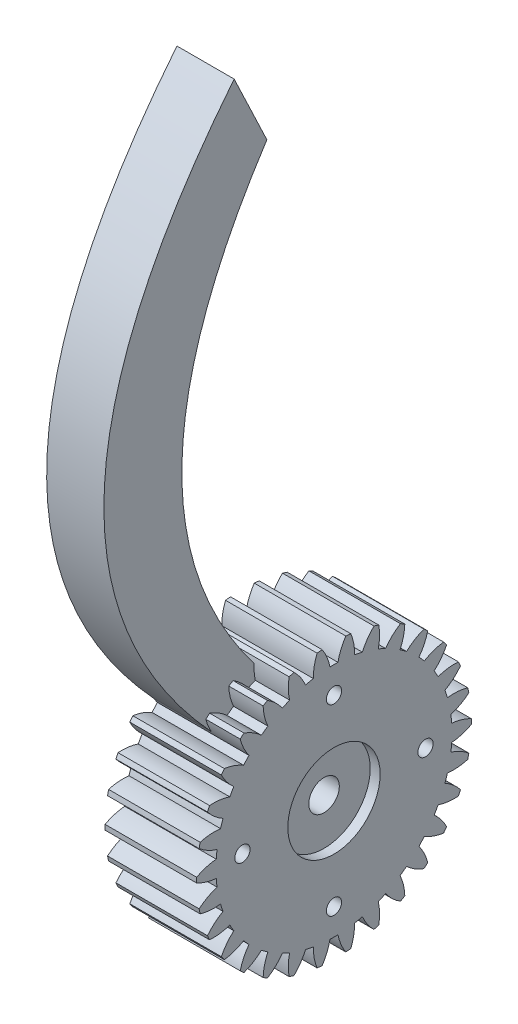
SolidWorks part; units mm, degrees
material "Nylon 101"
ref_plane "Plane1" through (0, 0, 0) normal (0, 0, 1) x (1, 0, 0)
ref_plane "Plane2" through (0, 0, 0) normal (0, 1, 0) x (1, 0, 0)
ref_plane "Plane3" through (0, 0, 0) normal (1, 0, 0) x (0, 0, -1)
other "Configuration Table"
sketch "HoldingSke" plane through (0, 0, 0) normal (0, 1, 0) x (1, 0, 0)
  line L0 (0, 0) -> (0.7698, -0.4444)
  line L1 (-15, 0) -> (100, 0) construction
  line L2 (0, 0) -> (-2.1039, 2.3779)
  line L3 (0, 0) -> (-11.863, 4.5341)
  line L4 (0, 0) -> (7.479, 4.318)
  line L5 (0, 0) -> (-46.8476, -17.4728)
  line L6 (0, 0) -> (-9.9476, -6.7116)
  line L7 (-2.1039, 2.3779) -> (8.6586, 51.2059)
  line L8 (-76.2, 54.61) -> (-75.5, 54.61)
  line L9 (-71.009, 38.7566) -> (-53.1078, 45.2721)
  line L10 (-76.2, 71.12) -> (104.1128, 71.12)
  line L11 (0, 0) -> (-12, 0)
  line L12 (-76.2, 101.6) -> (-76.158, 101.6)
  line L13 (24.9733, 27.94) -> (52.9518, 28.4284)
  line L14 (24.9733, 27.94) -> (24.9743, 27.94)
  line L15 (24.9733, 27.94) -> (100.4006, 29.5858)
  line L16 (-63.627, -1.125) -> (-12.827, -1.125)
  circle A0 centre (0, 0) radius 2
  circle A1 centre (0, 0) radius 15.4677
  circle A2 centre (0, 0) radius 37.5
  circle A3 centre (0, 0) radius 2
  dimension "MHD" = 30.9355
  dimension "Hub_dia" = 75
  dimension "Bore" = 4
  dimension "MBD" = 4
  dimension "Num_teeth" = 30
  dimension "Pitch" = 0.8889
  dimension "Overall_len" = 50
  dimension "Show_teeth" = 30
  dimension "Thickness" = 12
  dimension "OAL" = 50.0001
  dimension "T_dim" = 0.7
  dimension "Ap" = 20
  dimension "H" = 19.05
  dimension "Pitch_radius" = 180.3128
  dimension "Width" = 12
  dimension "Backlash" = 0.042
  dimension "Addendum_fac" = 1
  dimension "Dedendum_fac" = 1.25
  dimension "Clearance_fac" = 0.25
  dimension "Dedendum_add" = 0.001
  dimension "Module" = 1.125
sketch "BasProSke" plane through (0, 0, 0) normal (0, 1, 0) x (1, 0, 0)
  line L0 (-10, 0) -> (60, 0) construction
  line L1 (0, 0) -> (0, 18)
  line L2 (0, 0) -> (12, 0)
  line L3 (12, 0) -> (12, 18)
  line L4 (12, 18) -> (0, 18)
  dimension "Thickness" = 12
  dimension "Diameter" = 36
revolve "Base-Revolve" add sketch "BasProSke" angle 360 about L0
sketch "TooCutSke" plane through (0, 0, 0) normal (1, 0, 0) x (0, 0, -1)
  line L1 (0, 0) -> (0, 107) construction
  line L2 (0, 0) -> (-0.9567, 16.8479) construction
  line L3 (0, 0) -> (-3.5238, 33.5265) construction
  line L4 (-0.9567, 16.8479) -> (-1.7619, 16.7632) construction
  arc A0 (0.5235, 15.4589) -> (-0.5235, 15.4589) centre (0, 0) ccw
  arc A1 (1.5687, 17.957) -> (-1.5687, 17.957) centre (0, 0) ccw
  circle A2 centre (0, 0) radius 16.875 construction
  circle A3 centre (0, 0) radius 15.8573 construction
  arc A4 (-0.5235, 15.4589) -> (-1.5687, 17.957) centre (-7.1465, 14.1556) ccw
  arc A5 (1.5687, 17.957) -> (0.5235, 15.4589) centre (7.1465, 14.1556) ccw
  dimension "Root_dia" = 30.9355
  dimension "Overcut_dia" = 36.0508
  dimension "Pitch_dia" = 33.75
  dimension "Base_dia" = 31.7146
  dimension "Flank_rad" = 6.75
  dimension "Half_ang" = 6
  dimension "Half_CT" = 0.8097
extrude "ToothCut" cut sketch "TooCutSke" along normal through all
fillet "Breaks" [suppressed] radius 0.0225
fillet "RootFillets" [suppressed] radius 0.2822
pattern_circular "TeethCuts" count 30 every 12 about axis through (-10, 0, 0) along (1, 0, 0) of "ToothCut", "RootFillets", "Breaks"
sketch "HubNeaOneSke" plane through (0, 0, 0) normal (-1, 0, 0) x (0, 0, 1)
  circle A0 centre (0, 0) radius 15.4677
  dimension "Diameter" = 30.9355
extrude "HubNearOne" [suppressed] add sketch "HubNeaOneSke" along normal blind 38.0001
sketch "HubNeaBotSke" plane through (0, 0, 0) normal (-1, 0, 0) x (0, 0, 1)
  circle A0 centre (0, 0) radius 15.4677
  dimension "Diameter" = 30.9355
extrude "HubNearBoth" [suppressed] add sketch "HubNeaBotSke" along normal blind 19
ref_plane "FarPln" through (12, 0, 0) normal (1, 0, 0) x (0, 0, -1)
sketch "HubFarSke" plane through (12, 0, 0) normal (1, 0, 0) x (0, 0, -1)
  circle A0 centre (0, 0) radius 15.4677
  dimension "Diameter" = 30.9355
extrude "HubFar" [suppressed] add sketch "HubFarSke" along normal blind 19
sketch "BorSke" plane through (0, 0, 0) normal (1, 0, 0) x (0, 0, -1)
  circle A0 centre (0, 0) radius 2
  dimension "Diameter" = 4
extrude "Bore" cut sketch "BorSke" along normal mid plane 100.0001
sketch "KeySke" plane through (0, 0, 0) normal (1, 0, 0) x (0, 0, -1)
  line L0 (-0.8, 0) -> (-0.8, 2.7)
  line L1 (-0.8, 2.7) -> (0.8, 2.7)
  line L2 (0.8, 2.7) -> (0.8, 0)
  line L3 (0, 0) -> (0, 34) construction
  line L4 (-0.8, 0) -> (0.8, 0)
  dimension "Offset" = 2.7
  dimension "Width" = 1.6
extrude "Keyway" [suppressed] cut sketch "KeySke" along normal mid plane 100.0001
pattern_circular "Keyway2" [suppressed] count 2 every 90 about axis through (-10, 0, 0) along (1, 0, 0)
sketch "Sketch1" plane through (12, 0, 0) normal (1, 0, 0) x (0, 0, -1)
  circle A0 centre (0, 0) radius 6.05
  dimension "D2" = 12.1
extrude "Cut-Extrude1" cut sketch "Sketch1" against normal blind 1.3
sketch "Sketch2" plane through (12, 0, 0) normal (1, 0, 0) x (0, 0, -1)
  circle A0 centre (0, 7.5871) radius 0.003
  circle A1 centre (0, 12) radius 1
  circle A2 centre (12, 0) radius 1
  circle A3 centre (0, -12) radius 1
  circle A4 centre (-12, 0) radius 1
  point P14 (0, 0)
  dimension "D1" = 2
  dimension "D2" = 12
  dimension "D3" = 4
extrude "Cut-Extrude2" cut sketch "Sketch2" against normal through all
sketch "Sketch4" plane through (0, 0, 0) normal (-1, 0, 0) x (0, 0, 1)
  line L0 (-5, 5) -> (5, 5)
  line L1 (4.2917, 74.9282) -> (8.5798, 83.9621)
  spline S0 degree 2 poles (5, 5) (44.4284, 39.5045) (8.5798, 83.9621) knots 0 0 0 1 1 1
  spline S1 degree 2 poles (-5, 5) (30.521, 34.8856) (4.2917, 74.9282) knots 0 0 0 1 1 1
  dimension "D1" = 19.6846
  dimension "D2" = 10
  dimension "D3" = 5
  dimension "D4" = 10
  dimension "D5" = 5
  dimension "D6" = 30
  dimension "D7" = 69.9282
extrude "Boss-Extrude1" add sketch "Sketch4" against normal blind 7.5
equation "' \"Module@HoldingSke\" = 6.35"
equation "' \"Num_teeth@HoldingSke\" = 12"
equation "' \"Ap@HoldingSke\" =  20"
equation "' \"Ap@HoldingSke\" = 20"
equation "' \"Width@HoldingSke\" = 0.5 * 25.4"
equation "' \"Hub_dia@HoldingSke\"= 1 * 25.4"
equation "' \"Hub_dia@HoldingSke\" = 1 * 25.4"
equation "' \"Overall_len@HoldingSke\" = 1.0 * 25.4"
equation "' \"Bore@HoldingSke\" = 0.75 * 25.4"
equation "' \"T_dim@HoldingSke\" = 0.1 * 25.4"
equation "' \"Width@KeySke\" = 0.25 * 25.4"
equation "' \"Show_teeth@HoldingSke\" = 13"
equation "' \"Backlash@HoldingSke\" = 0.009 * 25.4"
equation "' \"Addendum_fac@HoldingSke\" = 1.0"
equation "' \"Dedendum_fac@HoldingSke\" = 1.25"
equation "' \"Dedendum_add@HoldingSke\" = 0.00005 * 25.4"
equation "' \"Clearance_fac@HoldingSke\" = 0.25"
equation "\"Pitch@HoldingSke\" = 1 / \"Module@HoldingSke\""
equation "\"Overcut_dia@TooCutSke\" = (\"Num_teeth@HoldingSke\" + 2 * \"Addendum_fac@HoldingSke\") / \"Pitch@HoldingSke\" + 0.002 * 25.4"
equation "\"Pitch_dia@TooCutSke\" = \"Num_teeth@HoldingSke\" / \"Pitch@HoldingSke\""
equation "\"Base_dia@TooCutSke\" = \"Num_teeth@HoldingSke\" / \"Pitch@HoldingSke\" * cos((\"Ap@HoldingSke\"  * 3.14159265 / 180))"
equation "\"Root_dia@TooCutSke\" = (\"Num_teeth@HoldingSke\" + 2) / \"Pitch@HoldingSke\" - 2 * (\"Addendum_fac@HoldingSke\" + \"Dedendum_fac@HoldingSke\") / \"Pitch@HoldingSke\" - \"Dedendum_add@HoldingSke\" * 2"
equation "\"Half_ang@TooCutSke\" = 180 / \"Num_teeth@HoldingSke\""
equation "\"Half_CT@TooCutSke\" = \"Num_teeth@HoldingSke\" / \"Pitch@HoldingSke\" * sin((3.14159265 / 2 / \"Num_teeth@HoldingSke\")) / 2 - 7 * \"Backlash@HoldingSke\" / 4"
equation "\"Flank_rad@TooCutSke\" = \"Num_teeth@HoldingSke\" / \"Pitch@HoldingSke\" / 5"
equation "\"Radius@RootFillets\" = \"Clearance_fac@HoldingSke\" / \"Pitch@HoldingSke\" + \"Dedendum_add@HoldingSke\""
equation "\"Break_rad@Breaks\" = 0.02 / \"Pitch@HoldingSke\""
equation "\"Thickness@HoldingSke\" = \"Width@HoldingSke\""
equation "\"OAL@HoldingSke\" = \"Thickness@HoldingSke\""
equation "\"MHD@HoldingSke\" = (\"Num_teeth@HoldingSke\" + 2) / \"Pitch@HoldingSke\" - 2 * (\"Addendum_fac@HoldingSke\" + \"Dedendum_fac@HoldingSke\")  / \"Pitch@HoldingSke\" - \"Dedendum_add@HoldingSke\" * 2"
equation "\"MBD@HoldingSke\" = (\"Num_teeth@HoldingSke\" + 2) / \"Pitch@HoldingSke\" - 2 * (\"Addendum_fac@HoldingSke\" + \"Dedendum_fac@HoldingSke\")  / \"Pitch@HoldingSke\" - \"Dedendum_add@HoldingSke\" * 2 - 0.002 * 25.4"
equation "\"MHD@HoldingSke\" = ((sgn( \"MHD@HoldingSke\" - \"Hub_dia@HoldingSke\" )-1)*( \"MHD@HoldingSke\" - \"Hub_dia@HoldingSke\" ))/-2+ \"Hub_dia@HoldingSke\""
equation "\"MBD@HoldingSke\" = ((sgn( \"MBD@HoldingSke\" - \"Bore@HoldingSke\" )-1)*( \"MBD@HoldingSke\" - \"Bore@HoldingSke\" ))/-2+ \"Bore@HoldingSke\""
equation "\"OAL@HoldingSke\" = ((sgn( \"OAL@HoldingSke\" - \"Overall_len@HoldingSke\" )+1)*( \"OAL@HoldingSke\" - \"Overall_len@HoldingSke\" ))/2 + \"Overall_len@HoldingSke\" + 0.000002 * 25.4"
equation "\"Num_teeth@TeethCuts\" = int( \"Show_teeth@HoldingSke\" ) + 1"
equation "\"Num_teeth@TeethCuts\" = ((sgn( \"Num_teeth@TeethCuts\" - \"Num_teeth@HoldingSke\" )-1)*( \"Num_teeth@TeethCuts\" - \"Num_teeth@HoldingSke\" ))/-2+ \"Num_teeth@HoldingSke\""
equation "\"Num_teeth@TeethCuts\" = ((sgn( \"Num_teeth@TeethCuts\" - 2.0)+1)*( \"Num_teeth@TeethCuts\" - 2.0))/2 +2.0"
equation "\"Angle@TeethCuts\" = 360.0 / \"Num_teeth@HoldingSke\""
equation "\"Diameter@BasProSke\" = (\"Num_teeth@HoldingSke\" + 2 * \"Addendum_fac@HoldingSke\") / \"Pitch@HoldingSke\""
equation "\"Thickness@BasProSke\"  = \"Thickness@HoldingSke\""
equation "' \"Fillet_rad@BasProSke\" =  \"Thickness@HoldingSke\" * 0.05"
equation "' \"Fillet_rad@BasProSke\" = \"Thickness@HoldingSke\" * 0.05"
equation "\"MHD@HoldingSke\" = ((sgn( \"MHD@HoldingSke\" - \"Root_dia@TooCutSke\" )-1)*( \"MHD@HoldingSke\" - \"Root_dia@TooCutSke\" ))/-2+ \"Root_dia@TooCutSke\""
equation "\"Diameter@HubNeaOneSke\" = \"MHD@HoldingSke\""
equation "\"Length@HubNearOne\" = \"OAL@HoldingSke\" - \"Thickness@BasProSke\""
equation "\"Diameter@HubNeaBotSke\" = \"MHD@HoldingSke\""
equation "\"Length@HubNearBoth\" = ( \"OAL@HoldingSke\" - \"Thickness@BasProSke\" ) / 2.0"
equation "\"Thickness@FarPln\" = \"Thickness@BasProSke\""
equation "\"Diameter@HubFarSke\" = \"MHD@HoldingSke\""
equation "\"Length@HubFar\" = ( \"OAL@HoldingSke\" - \"Thickness@BasProSke\" ) / 2.0"
equation "\"Diameter@BorSke\" = \"MBD@HoldingSke\""
equation "\"D1@Bore\" = \"OAL@HoldingSke\" * 2.0"
equation "\"D1@Keyway\" = \"OAL@HoldingSke\" * 2.0"
equation "\"Offset@KeySke\" = \"T_dim@HoldingSke\" + \"MBD@HoldingSke\" / 2.0"
